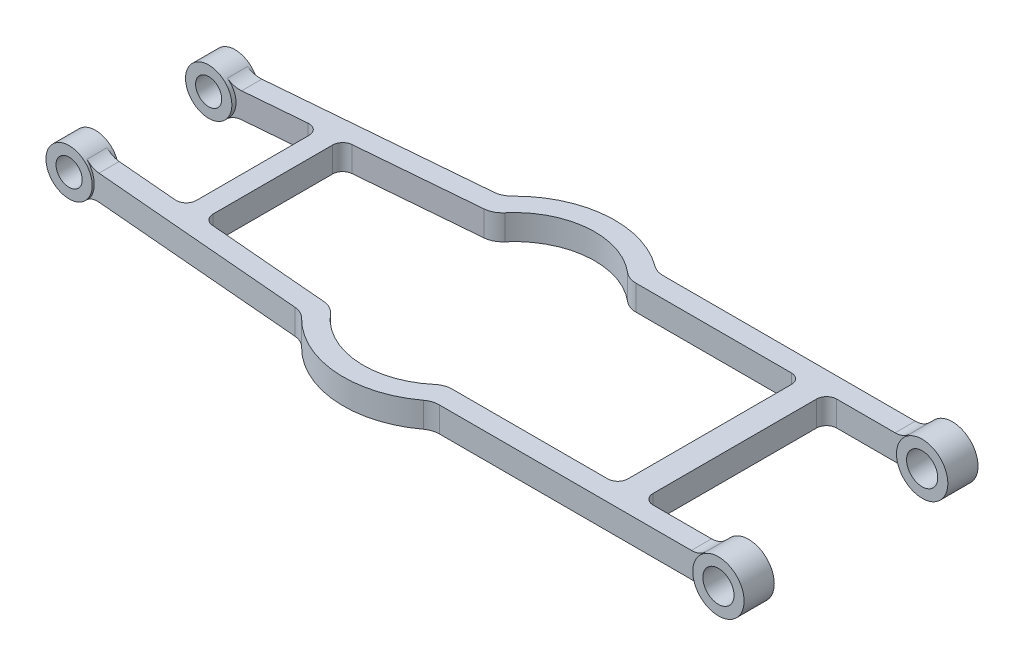
SolidWorks part; units mm, degrees
ref_plane "前视基准面" through (0, 0, 0) normal (0, 0, 1) x (1, 0, 0)
ref_plane "上视基准面" through (0, 0, 0) normal (0, 1, 0) x (1, 0, 0)
ref_plane "右视基准面" through (0, 0, 0) normal (1, 0, 0) x (0, 0, -1)
sketch "草图1" plane through (0, 0, 0) normal (0, 0, 1) x (1, 0, 0)
  circle A0 centre (0, 0) radius 2.6
  circle A1 centre (135.83, 0) radius 3.1
  circle A2 centre (0, 0) radius 4.6
  circle A3 centre (135.83, 0) radius 5.1
  dimension "D2" = 5.2
  dimension "D3" = 6.2
  dimension "D1" = 135.83
  dimension "D4" = 2
extrude "凸台-拉伸1" add sketch "草图1" along normal mid plane 33 contours A2 A0
sketch "草图2" plane through (0, 0, 0) normal (0, 0, 1) x (1, 0, 0)
  circle A1 centre (135.83, 0) radius 5.1
  circle A2 centre (135.83, 0) radius 5.1
  circle A3 centre (0, 0) radius 4.6
  circle A4 centre (0, 0) radius 4.6 construction
  circle A5 centre (135.83, 0) radius 3.1
  circle A6 centre (135.83, 0) radius 3.1
  circle A7 centre (0, 0) radius 2.6
  circle A8 centre (0, 0) radius 2.6 construction
  dimension "D1" = 0
  dimension "D2" = 0
  dimension "D3" = 0
  dimension "D4" = 0
extrude "凸台-拉伸2" add sketch "草图2" along normal mid plane 46.5 separate body
sketch "草图3" plane through (0, 0, 0) normal (0, 1, 0) x (1, 0, 0)
  line L0 (0, 0) -> (136.2148, 0) construction
  line L1 (132.1835, 20.25) -> (77.1835, 20.25) construction
  line L3 (3.5, 14) -> (50.7522, 18) construction
  line L4 (132.1835, 22.25) -> (77.9398, 22.25)
  line L5 (3.6687, 12.0071) -> (47.6619, 15.7313)
  line L6 (132.1835, 18.25) -> (81.5359, 18.25)
  line L7 (3.3313, 15.9929) -> (49.7341, 19.921)
  line L8 (140.93, 23.25) -> (130.73, 23.25) construction
  line L9 (3.3313, 15.9929) -> (3.6687, 12.0071)
  line L10 (3.3313, 15.9929) -> (50.5835, 19.9929) construction
  line L11 (3.6687, 12.0071) -> (50.9209, 16.0071) construction
  line L12 (132.1835, 22.25) -> (77.1835, 22.25) construction
  line L13 (132.1835, 18.25) -> (77.1835, 18.25) construction
  line L14 (132.1835, -18.25) -> (81.5359, -18.25)
  line L15 (132.1835, -22.25) -> (77.9398, -22.25)
  line L16 (3.6687, -12.0071) -> (47.6619, -15.7313)
  line L17 (3.3313, -15.9929) -> (3.6687, -12.0071)
  line L18 (3.3313, -15.9929) -> (49.7341, -19.921)
  line L19 (132.1835, -18.25) -> (132.1835, -22.25)
  line L20 (132.1835, 20.25) -> (77.1835, 20.25) construction
  line L21 (132.1835, 22.25) -> (132.1835, 18.25)
  line L22 (47.6619, 15.7313) -> (51.8288, 16.084)
  line L23 (81.5359, 18.25) -> (76.3771, 18.25)
  line L26 (81.5359, -18.25) -> (76.3771, -18.25)
  line L28 (47.6619, -15.7313) -> (51.8288, -16.084)
  circle A0 centre (65, 7) radius 18 construction
  arc A1 (46.265, 0) -> (83.735, 0) centre (65, 7) ccw construction
  arc A2 (49.1081, 5.1429) -> (80.8919, 5.1429) centre (65, 7) ccw construction
  arc A3 (79.3875, 0) -> (80.8919, -5.1429) centre (65, -7) cw construction
  arc A4 (80.8919, 5.1429) -> (83.735, 0) centre (65, -7) cw construction
  circle A5 centre (65, 7) radius 16 construction
  circle A6 centre (65, 7) radius 20 construction
  arc A7 (76.3771, 18.25) -> (51.8288, 16.084) centre (65, 7) ccw
  arc A9 (77.9398, -22.25) -> (49.7341, -19.921) centre (65, -7) cw
  arc A10 (76.3771, -18.25) -> (51.8288, -16.084) centre (65, -7) cw
  arc A11 (49.1081, -5.1429) -> (50.6125, 0) centre (65, -7) cw construction
  arc A12 (46.265, 0) -> (49.1081, 5.1429) centre (65, -7) cw construction
  arc A13 (77.9398, 22.25) -> (49.7341, 19.921) centre (65, 7) ccw
  dimension "D7" = 36
  dimension "D9" = 65
  dimension "D3" = 1
  dimension "D4" = 14
  dimension "D5" = 3.5
  dimension "D6" = 18
  dimension "D8" = 7
  dimension "D10" = 55
  dimension "D1" = 2
  dimension "D2" = 2
extrude "凸台-拉伸3" add sketch "草图3" along normal mid plane 5
sketch "草图4" plane through (0, 0, 0) normal (0, 0, 1) x (1, 0, 0)
  line L0 (20, 2.5) -> (20, -2.5)
  line L1 (3.8613, 2.5) -> (49.7341, 2.5) construction
  line L2 (3.8613, -2.5) -> (49.7341, -2.5) construction
  line L3 (20, -2.5) -> (24, -2.5)
  line L4 (24, -2.5) -> (24, 2.5)
  line L5 (24, 2.5) -> (20, 2.5)
  dimension "D1" = 4
  dimension "D2" = 20
extrude "凸台-拉伸4" add sketch "草图4" along normal mid plane 28
sketch "草图5" plane through (0, 0, 0) normal (0, 0, 1) x (1, 0, 0)
  line L0 (110.83, 2.5) -> (110.83, -2.5)
  line L1 (77.9398, 2.5) -> (131.3848, 2.5) construction
  line L2 (77.9398, -2.5) -> (131.3848, -2.5) construction
  line L3 (110.83, -2.5) -> (115.83, -2.5)
  line L4 (115.83, -2.5) -> (115.83, 2.5)
  line L5 (115.83, 2.5) -> (110.83, 2.5)
  circle A0 centre (135.83, 0) radius 3.1 construction
  dimension "D1" = 5
  dimension "D2" = 20
extrude "凸台-拉伸5" add sketch "草图5" along normal mid plane 42
sketch "草图7" plane through (0, 0, 0) normal (0, 1, 0) x (1, 0, 0)
  line L0 (115.83, 18.25) -> (131.3848, 18.25) construction
  line L1 (-11.6251, -11.25) -> (11.6251, -11.25)
  line L2 (-11.6251, -11.25) -> (-11.6251, 11.25)
  line L3 (-11.6251, 11.25) -> (11.6251, 11.25)
  line L4 (11.6251, -11.25) -> (11.6251, 11.25)
  line L5 (-11.6251, -11.25) -> (11.6251, 11.25) construction
  line L6 (-11.6251, 11.25) -> (11.6251, -11.25) construction
  line L7 (117.209, -17.25) -> (145.432, -17.25)
  line L8 (117.209, -17.25) -> (117.209, 17.25)
  line L9 (117.209, 17.25) -> (145.432, 17.25)
  line L10 (145.432, -17.25) -> (145.432, 17.25)
  line L11 (117.209, -17.25) -> (145.432, 17.25) construction
  line L12 (117.209, 17.25) -> (145.432, -17.25) construction
  point P0 (0, 0)
  point P6 (131.3205, 0)
  dimension "D1" = 22.5
  dimension "D2" = 1
extrude "切除-拉伸1" cut sketch "草图7" against normal mid plane 42
fillet "圆角1" radius 2 8 edges at (115.83, 0, 18.25) (110.83, 0, 18.25) (110.83, 0, -18.25) (115.83, 0, -18.25) (24, 0, 13.7282) (20, 0, 13.3896) (24, 0, -13.7282) (20, 0, -13.3896)
fillet "圆角2" radius 4 8 edges at (49.7341, 0, 19.921) (77.9398, 0, 22.25) (49.7341, 0, -19.921) (77.9398, 0, -22.25) (51.8288, 0, -16.084) (51.8288, 0, 16.084) (76.3771, 0, 18.25) (76.3771, 0, -18.25)
fillet "圆角3" radius 4 8 edges at (131.3848, 2.5, -20.25) (131.3848, 2.5, 20.25) (131.3848, -2.5, 20.25) (131.3848, -2.5, -20.25) (3.8613, -2.5, -14.0306) (3.8613, -2.5, 14.0306) (3.8613, 2.5, 14.0306) (3.8613, 2.5, -14.0306)
